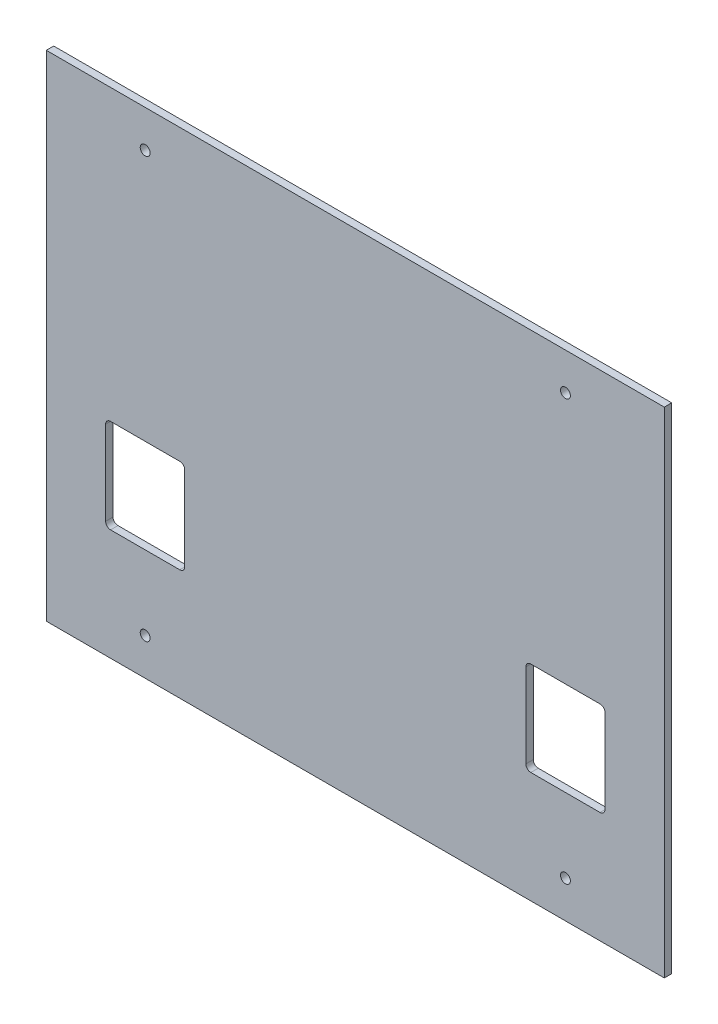
SolidWorks part; units mm, degrees
ref_plane "Front Plane" through (0, 0, 0) normal (0, 0, 1) x (1, 0, 0)
ref_plane "Top Plane" through (0, 0, 0) normal (0, 1, 0) x (1, 0, 0)
ref_plane "Right Plane" through (0, 0, 0) normal (1, 0, 0) x (0, 0, -1)
sketch "Sketch1" plane through (0, 0, 0) normal (0, 0, 1) x (1, 0, 0)
  line L1 (125, -100) -> (-125, -100)
  line L2 (125, -100) -> (125, 100)
  line L3 (125, 100) -> (-125, 100)
  line L4 (-125, -100) -> (-125, 100)
  line L5 (125, -100) -> (-125, 100) construction
  line L6 (125, 100) -> (-125, -100) construction
  point P0 (0, 0)
  dimension "D1" = 250
  dimension "D2" = 200
extrude "Boss-Extrude1" add sketch "Sketch1" along normal blind 3
sketch "Sketch3" plane through (0, 0, 3) normal (0, 0, 1) x (1, 0, 0)
  line L0 (-125, 100) -> (-125, -100) construction
  line L1 (125, 100) -> (-125, 100) construction
  line L2 (0, -1.65) -> (0, 1.65) construction
  circle A0 centre (-85, 85) radius 2
  circle A1 centre (-85, -85) radius 2
  circle A3 centre (-85, -425) radius 2
  circle A4 centre (85, -425) radius 2
  circle A6 centre (85, -85) radius 2
  circle A7 centre (85, 85) radius 2
  circle A8 centre (-85, -255) radius 2 [skipped]
  dimension "D1" = 40
  dimension "D2" = 15
  dimension "D3" = 170
  dimension "D4" = 4
extrude "Cut-Extrude2" cut sketch "Sketch3" against normal blind 3
sketch "Sketch4" plane through (0, 0, 0) normal (0, 0, -1) x (-1, 0, 0)
  line L0 (-97, -18) -> (-73, -18) construction
  line L1 (-99, -17) -> (-71, -17)
  line L2 (-101, -19) -> (-101, -53)
  line L3 (-99, -55) -> (-71, -55)
  line L4 (-69, -19) -> (-69, -53)
  line L5 (-100, -24) -> (-100, -21) construction
  line L6 (-70, -47) -> (-70, -25) construction
  line L7 (-97, -54) -> (-73, -54) construction
  line L8 (0, 1.65) -> (0, -1.65) construction
  line L9 (69, -19) -> (69, -53)
  line L10 (99, -55) -> (71, -55)
  line L11 (101, -19) -> (101, -53)
  line L12 (99, -17) -> (71, -17)
  arc A0 (-99, -55) -> (-101, -53) centre (-99, -53) cw
  arc A1 (-71, -55) -> (-69, -53) centre (-71, -53) ccw
  arc A2 (-69, -19) -> (-71, -17) centre (-71, -19) ccw
  arc A3 (-99, -17) -> (-101, -19) centre (-99, -19) ccw
  arc A4 (99, -17) -> (101, -19) centre (99, -19) cw
  arc A5 (69, -19) -> (71, -17) centre (71, -19) cw
  arc A6 (71, -55) -> (69, -53) centre (71, -53) cw
  arc A7 (99, -55) -> (101, -53) centre (99, -53) ccw
  dimension "D5" = 2
  dimension "D1" = 1
  dimension "D2" = 1
  dimension "D3" = 1
  dimension "D4" = 1
extrude "Cut-Extrude3" cut sketch "Sketch4" against normal blind 10
